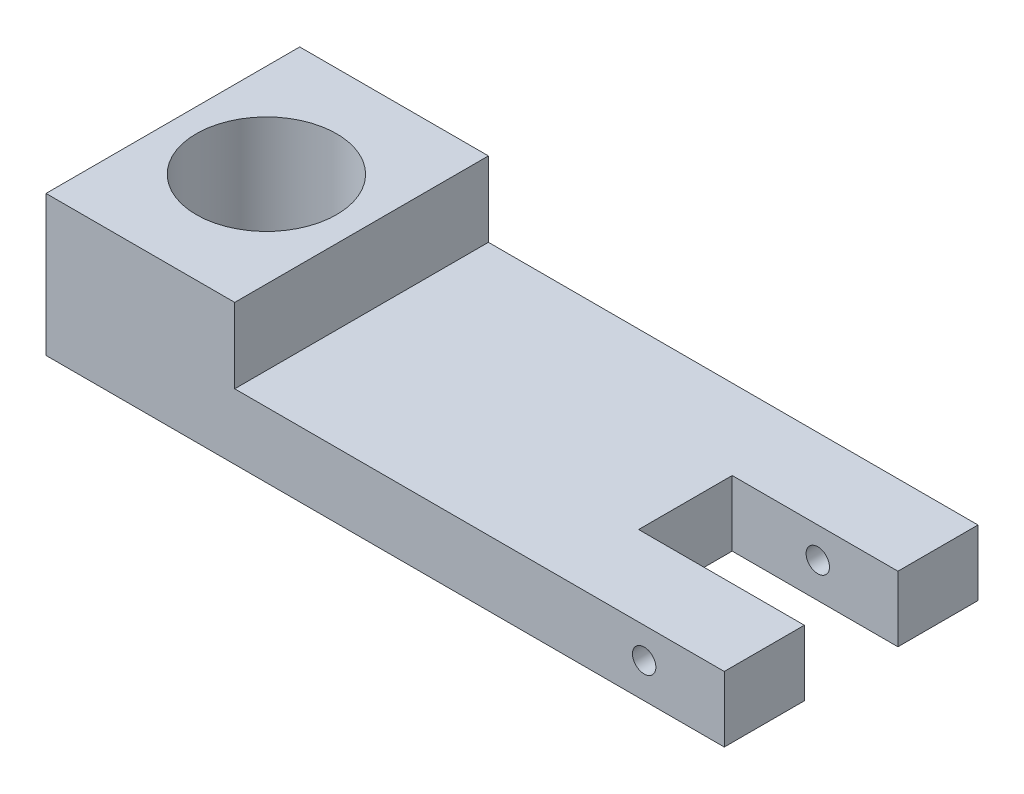
SolidWorks part; units mm, degrees
ref_plane "Спереди" through (0, 0, 0) normal (0, 0, 1) x (1, 0, 0)
ref_plane "Сверху" through (0, 0, 0) normal (0, 1, 0) x (1, 0, 0)
ref_plane "Справа" through (0, 0, 0) normal (1, 0, 0) x (0, 0, -1)
sketch "Эскиз1" plane through (0, 0, 0) normal (0, 1, 0) x (1, 0, 0)
  line L0 (-15, 0) -> (-15, 58.2175) construction
  line L1 (-20, 27.1196) -> (125, 27.1196)
  line L2 (-20, 27.1196) -> (-20, -27.1196)
  line L3 (-20, -27.1196) -> (125, -27.1196)
  line L4 (125, 27.1196) -> (125, -27.1196)
  circle A0 centre (0, 0) radius 15
  dimension "D1" = 30
  dimension "D2" = 5
extrude "Вытянуть1" add sketch "Эскиз1" along normal blind 14
sketch "Эскиз2" plane through (0, 0, 0) normal (0, 1, 0) x (1, 0, 0)
  line L1 (89.569, -10) -> (130.5426, -10)
  line L2 (89.569, 10) -> (130.5426, 10)
  line L3 (130.5426, -10) -> (130.5426, 10)
  line L5 (89.569, -10) -> (89.569, 10)
  dimension "D4" = 130.5426
extrude "Вырез-Вытянуть1" cut sketch "Эскиз2" along normal blind 50
sketch "Эскиз3" plane through (0, 0, 0) normal (0, 0, 1) x (1, 0, 0)
  circle A0 centre (107.8714, 7.4611) radius 2.5
  dimension "D1" = 5
extrude "Вырез-Вытянуть2" cut sketch "Эскиз3" against normal mid plane 72
sketch "Эскиз4" plane through (0, 14, 0) normal (0, 1, 0) x (1, 0, 0)
  line L0 (125, 27.1196) -> (-20, 27.1196) construction
  line L1 (-20, -27.1196) -> (20.3425, -27.1196)
  line L2 (-20, -27.1196) -> (-20, 27.1196)
  line L3 (-20, 27.1196) -> (20.3425, 27.1196)
  line L4 (20.3425, -27.1196) -> (20.3425, 27.1196)
  circle A0 centre (0, 0) radius 15
extrude "Вытянуть2" add sketch "Эскиз4" along normal blind 16
